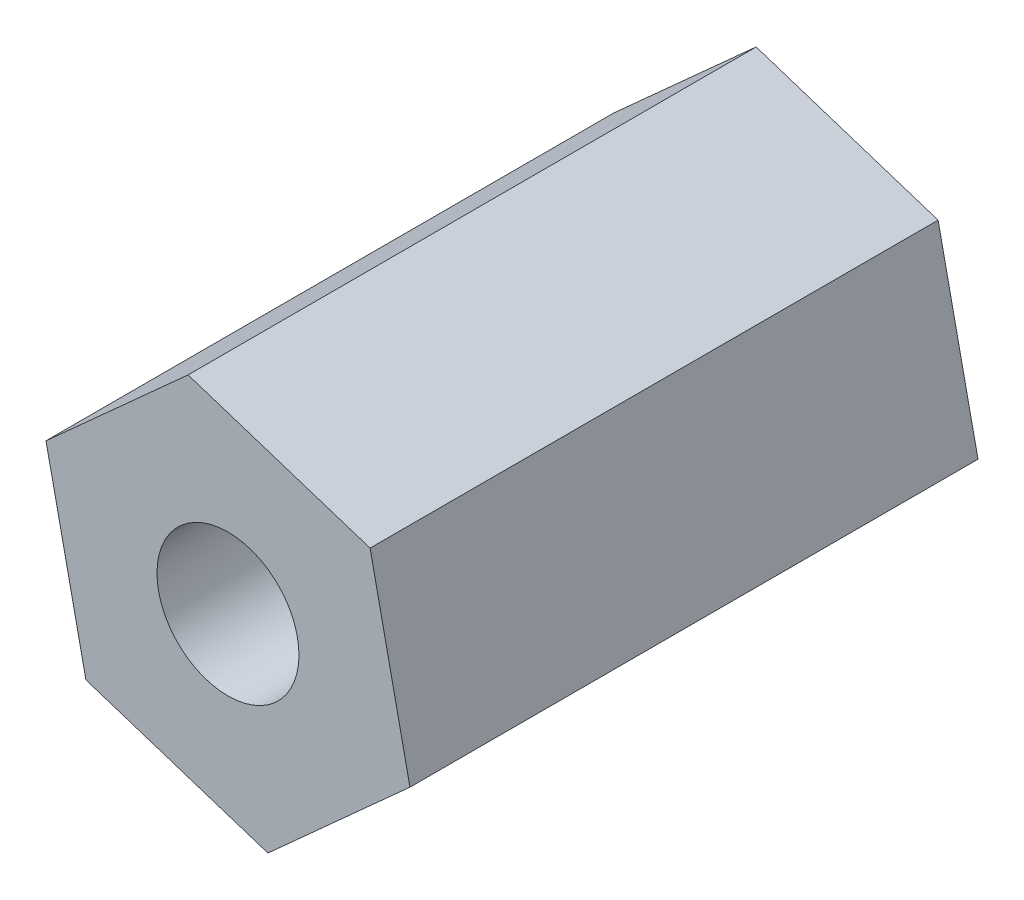
SolidWorks part; units mm, degrees
ref_plane "Plano frontal" through (0, 0, 0) normal (0, 0, 1) x (1, 0, 0)
ref_plane "Plano superior" through (0, 0, 0) normal (0, 1, 0) x (1, 0, 0)
ref_plane "Plano direito" through (0, 0, 0) normal (1, 0, 0) x (0, 0, -1)
sketch "Esboço1" plane through (0, 0, 0) normal (0, 0, 1) x (1, 0, 0)
  line L7 (-0.8428, 3.9526) -> (-3.8444, 1.2464)
  line L8 (-3.8444, 1.2464) -> (-3.0017, -2.7062)
  line L9 (-3.0017, -2.7062) -> (0.8428, -3.9526)
  line L10 (0.8428, -3.9526) -> (3.8444, -1.2464)
  line L11 (3.8444, -1.2464) -> (3.0017, 2.7062)
  line L12 (3.0017, 2.7062) -> (-0.8428, 3.9526)
  circle A1 centre (0, 0) radius 3.5 construction
  dimension "D2" = 7
extrude "Ressalto-extrusão1" add sketch "Esboço1" along normal blind 12
sketch "Esboço3" plane through (0, 0, 0) normal (0, 0, -1) x (-1, 0, 0)
  circle A0 centre (0, 0) radius 1.5
  dimension "D1" = 3
extrude "Corte-extrusão2" cut sketch "Esboço3" against normal up to next
